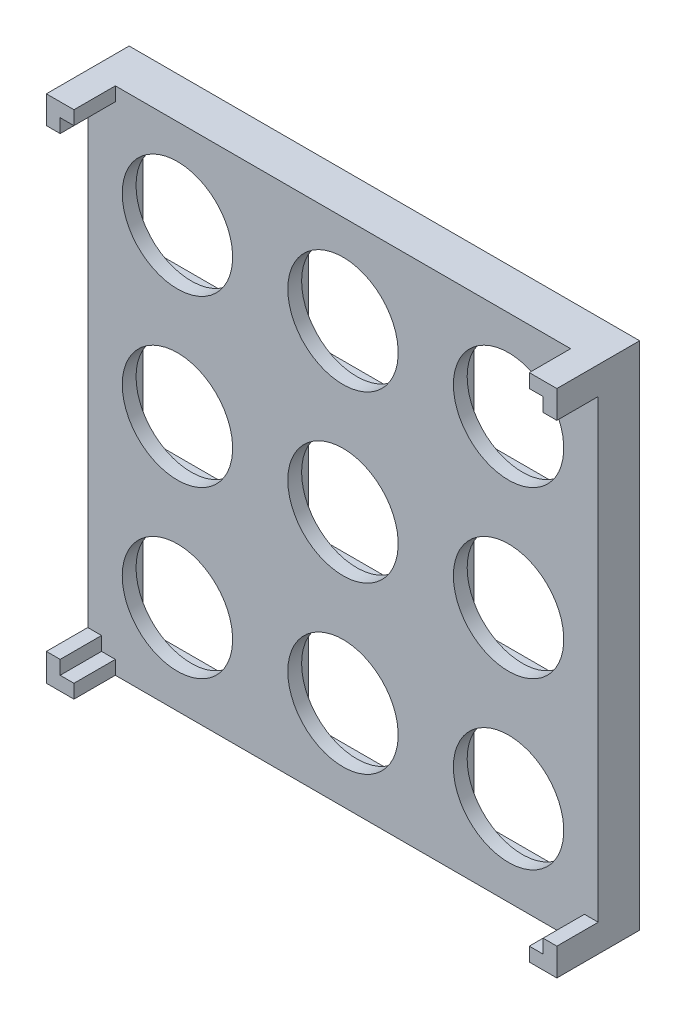
SolidWorks part; units mm, degrees
ref_plane "Front Plane" through (0, 0, 0) normal (0, 0, 1) x (1, 0, 0)
ref_plane "Top Plane" through (0, 0, 0) normal (0, 1, 0) x (1, 0, 0)
ref_plane "Right Plane" through (0, 0, 0) normal (1, 0, 0) x (0, 0, -1)
sketch "Sketch5" plane through (0, 0, 0) normal (0, 0, 1) x (1, 0, 0)
  line L1 (-61.8384, 110.0209) -> (123.1616, 110.0209)
  line L2 (-61.8384, 110.0209) -> (-61.8384, -74.9791)
  line L3 (-61.8384, -74.9791) -> (123.1616, -74.9791)
  line L4 (123.1616, 110.0209) -> (123.1616, -74.9791)
  dimension "D1" = 185
  dimension "D2" = 185
extrude "Boss-Extrude5" add sketch "Sketch5" along normal blind 30
sketch "Sketch6" plane through (0, 0, 0) normal (0, 0, -1) x (-1, 0, 0)
  line L0 (61.8384, 110.0209) -> (61.8384, -74.9791) construction
  line L1 (56.8384, 105.0209) -> (1.8384, 105.0209)
  line L2 (56.8384, 105.0209) -> (56.8384, 50.0209)
  line L3 (56.8384, 50.0209) -> (1.8384, 50.0209)
  line L4 (1.8384, 105.0209) -> (1.8384, 50.0209)
  line L5 (-123.1616, 110.0209) -> (61.8384, 110.0209) construction
  line L6 (56.8384, 50.0209) -> (61.8384, 50.0209) construction
  line L7 (1.8384, 105.0209) -> (1.8384, 110.0209) construction
  line L8 (56.8384, 45.0209) -> (56.8384, -9.9791)
  line L9 (56.8384, -9.9791) -> (1.8384, -9.9791)
  line L10 (56.8384, 45.0209) -> (1.8384, 45.0209)
  line L11 (1.8384, 45.0209) -> (1.8384, -9.9791)
  line L12 (56.8384, -9.9791) -> (61.8384, -9.9791) construction
  line L13 (56.8384, -14.9791) -> (1.8384, -14.9791)
  line L14 (56.8384, -69.9791) -> (1.8384, -69.9791)
  line L15 (56.8384, -14.9791) -> (56.8384, -69.9791)
  line L16 (1.8384, -14.9791) -> (1.8384, -69.9791)
  line L17 (-3.1616, 45.0209) -> (-58.1616, 45.0209)
  line L18 (-58.1616, 105.0209) -> (-58.1616, 50.0209)
  line L19 (-3.1616, 50.0209) -> (-58.1616, 50.0209)
  line L20 (-3.1616, 45.0209) -> (-3.1616, -9.9791)
  line L21 (-3.1616, 105.0209) -> (-3.1616, 50.0209)
  line L22 (-3.1616, -14.9791) -> (-58.1616, -14.9791)
  line L23 (-3.1616, -9.9791) -> (-58.1616, -9.9791)
  line L24 (-3.1616, -14.9791) -> (-3.1616, -69.9791)
  line L25 (-58.1616, 45.0209) -> (-58.1616, -9.9791)
  line L26 (-3.1616, -69.9791) -> (-58.1616, -69.9791)
  line L27 (-3.1616, 105.0209) -> (-58.1616, 105.0209)
  line L28 (-58.1616, -14.9791) -> (-58.1616, -69.9791)
  line L29 (-58.1616, 105.0209) -> (-58.1616, 110.0209) construction
  line L30 (-63.1616, -14.9791) -> (-63.1616, -69.9791)
  line L31 (-63.1616, 105.0209) -> (-118.1616, 105.0209)
  line L32 (-63.1616, 50.0209) -> (-118.1616, 50.0209)
  line L33 (-63.1616, 45.0209) -> (-118.1616, 45.0209)
  line L34 (-63.1616, 45.0209) -> (-63.1616, -9.9791)
  line L35 (-63.1616, -9.9791) -> (-118.1616, -9.9791)
  line L36 (-63.1616, 105.0209) -> (-63.1616, 50.0209)
  line L37 (-63.1616, -14.9791) -> (-118.1616, -14.9791)
  line L38 (-63.1616, -69.9791) -> (-118.1616, -69.9791)
  line L39 (-118.1616, 105.0209) -> (-118.1616, 50.0209)
  line L40 (-118.1616, -14.9791) -> (-118.1616, -69.9791)
  line L41 (-118.1616, 45.0209) -> (-118.1616, -9.9791)
  dimension "D1" = 55
  dimension "D2" = 5
  dimension "D3" = 5
  dimension "D4" = 55
extrude "Cut-Extrude2" cut sketch "Sketch6" against normal blind 10 contours L10 L11 L9 L8 | L13 L16 L14 L15 | L22 L28 L26 L24 | L17 L25 L23 L20 | L21 L27 L18 L19 | L31 L39 L32 L36 | L33 L41 L35 L34 | L37 L40 L38 L30 | L2 L1 L4 L3
sketch "Sketch7" plane through (0, 0, 10) normal (0, 0, -1) x (-1, 0, 0)
  line L0 (-118.1616, 77.5209) -> (-63.1616, 77.5209) construction
  line L1 (-118.1616, 105.0209) -> (-118.1616, 50.0209) construction
  line L2 (-63.1616, 105.0209) -> (-63.1616, 50.0209) construction
  line L3 (-90.6616, 50.0209) -> (-90.6616, 105.0209) construction
  line L4 (-63.1616, 50.0209) -> (-118.1616, 50.0209) construction
  line L5 (-63.1616, 105.0209) -> (-118.1616, 105.0209) construction
  circle A0 centre (-90.6616, 77.5209) radius 20
  circle A1 centre (-30.6616, 77.5209) radius 20
  circle A2 centre (29.3384, 77.5209) radius 20
  circle A3 centre (29.3384, 17.5209) radius 20
  circle A4 centre (-30.6616, 17.5209) radius 20
  circle A5 centre (-90.6616, 17.5209) radius 20
  circle A6 centre (29.3384, -42.4791) radius 20
  circle A7 centre (-90.6616, -42.4791) radius 20
  circle A8 centre (-30.6616, -42.4791) radius 20
  dimension "D1" = 40
extrude "Cut-Extrude3" cut sketch "Sketch7" against normal through all
sketch "Sketch8" plane through (0, 0, 30) normal (0, 0, 1) x (1, 0, 0)
  line L0 (123.1616, -74.9791) -> (123.1616, 110.0209) construction
  line L1 (118.1616, 105.0209) -> (-56.8384, 105.0209)
  line L2 (118.1616, 105.0209) -> (118.1616, -69.9791)
  line L3 (118.1616, -69.9791) -> (-56.8384, -69.9791)
  line L4 (-56.8384, 105.0209) -> (-56.8384, -69.9791)
  line L5 (-61.8384, -74.9791) -> (123.1616, -74.9791) construction
  line L6 (123.1616, 110.0209) -> (-61.8384, 110.0209) construction
  line L7 (-61.8384, 110.0209) -> (-61.8384, -74.9791) construction
  dimension "D1" = 5
  dimension "D2" = 5
  dimension "D3" = 5
  dimension "D4" = 5
extrude "Cut-Extrude4" cut sketch "Sketch8" against normal blind 15
sketch "Sketch9" plane through (0, 110.0209, 0) normal (0, 1, 0) x (1, 0, 0)
  line L0 (123.1616, -30) -> (-61.8384, -30) construction
  line L1 (113.1616, -30) -> (-51.8384, -30)
  line L2 (113.1616, -30) -> (113.1616, -15)
  line L3 (113.1616, -15) -> (-51.8384, -15)
  line L4 (-51.8384, -30) -> (-51.8384, -15)
  line L5 (123.1616, -30) -> (123.1616, 0) construction
  line L6 (-61.8384, -30) -> (-61.8384, 0) construction
  dimension "D1" = 10
  dimension "D2" = 10
  dimension "D3" = 15
extrude "Cut-Extrude6" cut sketch "Sketch9" against normal through all
sketch "Sketch11" plane through (-61.8384, 0, 0) normal (-1, 0, 0) x (0, 0, 1)
  line L0 (30, 110.0209) -> (30, -74.9791) construction
  line L1 (30, 100.0209) -> (15, 100.0209)
  line L2 (30, 100.0209) -> (30, -64.9791)
  line L3 (30, -64.9791) -> (15, -64.9791)
  line L4 (15, 100.0209) -> (15, -64.9791)
  line L5 (30, 110.0209) -> (0, 110.0209) construction
  line L6 (30, -74.9791) -> (0, -74.9791) construction
  dimension "D1" = 15
  dimension "D2" = 10
  dimension "D3" = 10
extrude "Cut-Extrude7" cut sketch "Sketch11" against normal through all
sketch "Sketch12" plane through (0, -74.9791, 0) normal (0, -1, 0) x (1, 0, 0)
  line L1 (113.1616, 15) -> (123.1616, 15)
  line L2 (113.1616, 15) -> (113.1616, 30)
  line L3 (113.1616, 30) -> (123.1616, 30)
  line L4 (123.1616, 15) -> (123.1616, 30)
